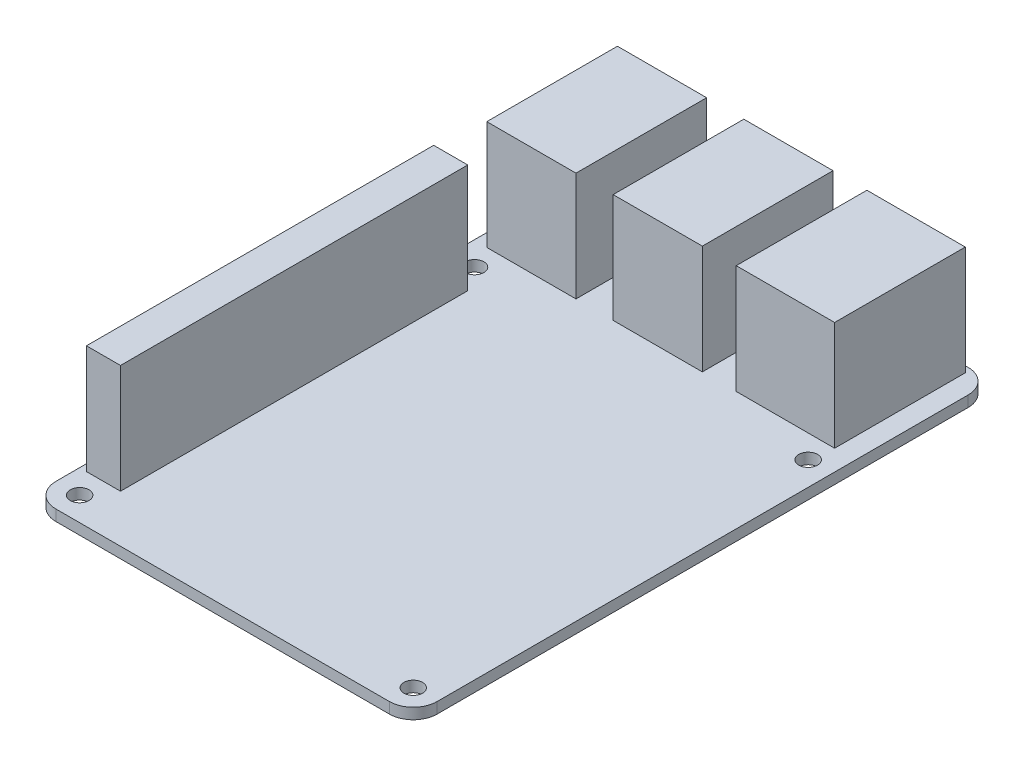
SolidWorks part; units mm, degrees
ref_plane "Front Plane" through (0, 0, 0) normal (0, 0, 1) x (1, 0, 0)
ref_plane "Top Plane" through (0, 0, 0) normal (0, 1, 0) x (1, 0, 0)
ref_plane "Right Plane" through (0, 0, 0) normal (1, 0, 0) x (0, 0, -1)
sketch "Sketch1" plane through (0, 0, 0) normal (0, 1, 0) x (1, 0, 0)
  line L1 (0, 0) -> (56, 0)
  line L2 (0, 0) -> (0, 85)
  line L3 (0, 85) -> (56, 85)
  line L4 (56, 0) -> (56, 85)
  circle A0 centre (3.5, 3.5) radius 1.375
  circle A1 centre (52.5, 3.5) radius 1.375
  circle A2 centre (52.5, 61.5) radius 1.375
  circle A3 centre (3.5, 61.5) radius 1.375
extrude "Boss-Extrude1" add sketch "Sketch1" along normal blind 1.6
fillet "Fillet1" radius 3.5 4 edges at (56, 0.8, -85) (0, 0.8, -85) (0, 0.8, 0) (56, 0.8, 0)
sketch "Sketch3" plane through (0, 1.6, 0) normal (0, 1, 0) x (1, 0, 0)
  line L1 (1.8885, 64.9067) -> (14.9885, 64.9067)
  line L2 (1.8885, 64.9067) -> (1.8885, 84.0963)
  line L3 (1.8885, 84.0963) -> (14.9885, 84.0963)
  line L4 (14.9885, 64.9067) -> (14.9885, 84.0963)
  line L5 (1.8885, 64.9067) -> (14.9885, 84.0963) construction
  line L6 (1.8885, 84.0963) -> (14.9885, 64.9067) construction
  line L7 (20.45, 64.9067) -> (33.55, 64.9067)
  line L8 (20.45, 64.9067) -> (20.45, 84.0963)
  line L9 (20.45, 84.0963) -> (33.55, 84.0963)
  line L10 (33.55, 64.9067) -> (33.55, 84.0963)
  line L11 (20.45, 64.9067) -> (33.55, 84.0963) construction
  line L12 (20.45, 84.0963) -> (33.55, 64.9067) construction
  line L13 (38.5257, 64.9067) -> (52.9743, 64.9067)
  line L14 (38.5257, 64.9067) -> (38.5257, 84.0963)
  line L15 (38.5257, 84.0963) -> (52.9743, 84.0963)
  line L16 (52.9743, 64.9067) -> (52.9743, 84.0963)
  line L17 (38.5257, 64.9067) -> (52.9743, 84.0963) construction
  line L18 (38.5257, 84.0963) -> (52.9743, 64.9067) construction
  point P0 (8.4385, 74.5015)
  point P5 (27, 74.5015)
  point P10 (45.75, 74.5015)
  point P15 (0, 0)
  point P16 (0, 0)
  point P17 (0, 0)
extrude "Boss-Extrude2" add sketch "Sketch3" along normal blind 16
sketch "Sketch5" plane through (0, 1.6, 0) normal (0, 1, 0) x (1, 0, 0)
  line L1 (1, 7) -> (6, 7)
  line L2 (1, 7) -> (1, 58)
  line L3 (1, 58) -> (6, 58)
  line L4 (6, 7) -> (6, 58)
  line L5 (1, 7) -> (6, 58) construction
  line L6 (1, 58) -> (6, 7) construction
  point P0 (3.5, 32.5)
  point P5 (0, 0)
  point P6 (0, 0)
  point P7 (0, 0)
  point P8 (0, 0)
extrude "Boss-Extrude3" add sketch "Sketch5" along normal blind 16
